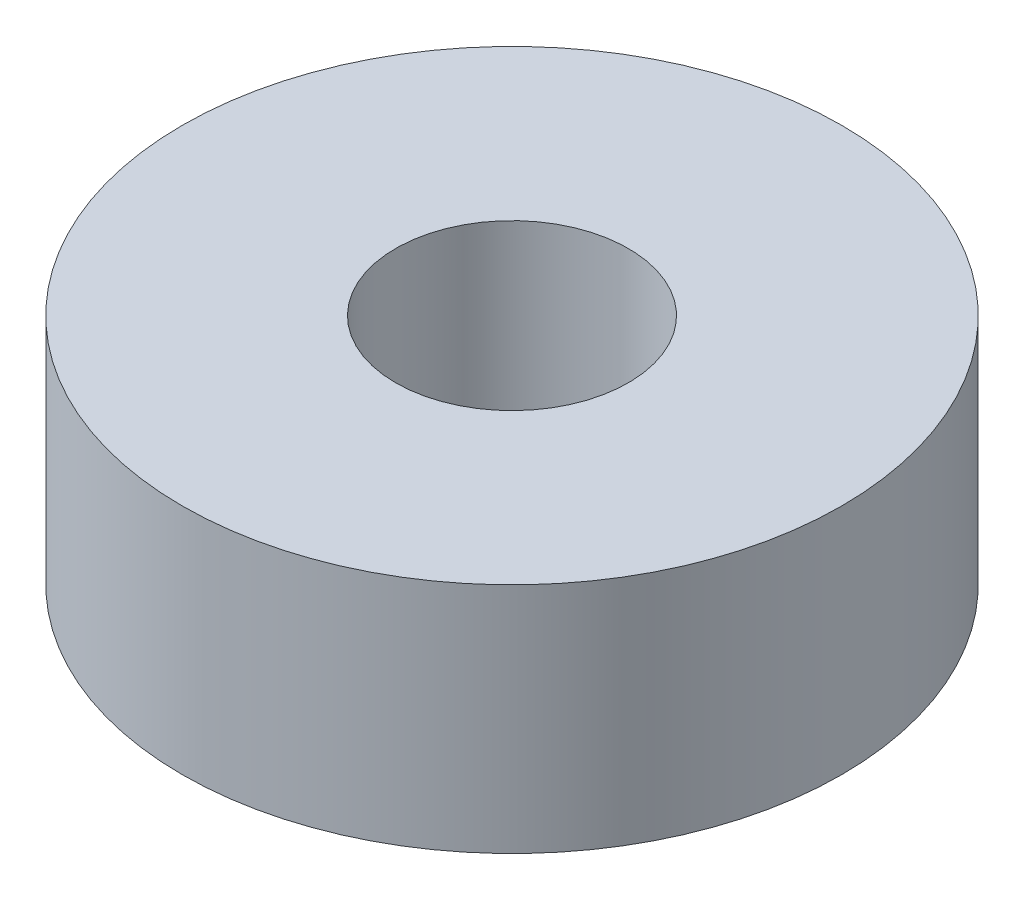
SolidWorks part; units mm, degrees
material "Plain Carbon Steel"
ref_plane "Front Plane" through (0, 0, 0) normal (0, 0, 1) x (1, 0, 0)
ref_plane "Top Plane" through (0, 0, 0) normal (0, 1, 0) x (1, 0, 0)
ref_plane "Right Plane" through (0, 0, 0) normal (1, 0, 0) x (0, 0, -1)
sketch "Sketch1" plane through (0, 0, 0) normal (0, 1, 0) x (1, 0, 0)
  circle A0 centre (0, 0) radius 8.5
  circle A1 centre (0, 0) radius 3
  dimension "D1" = 17
  dimension "D2" = 6
extrude "Boss-Extrude1" add sketch "Sketch1" along normal blind 6
